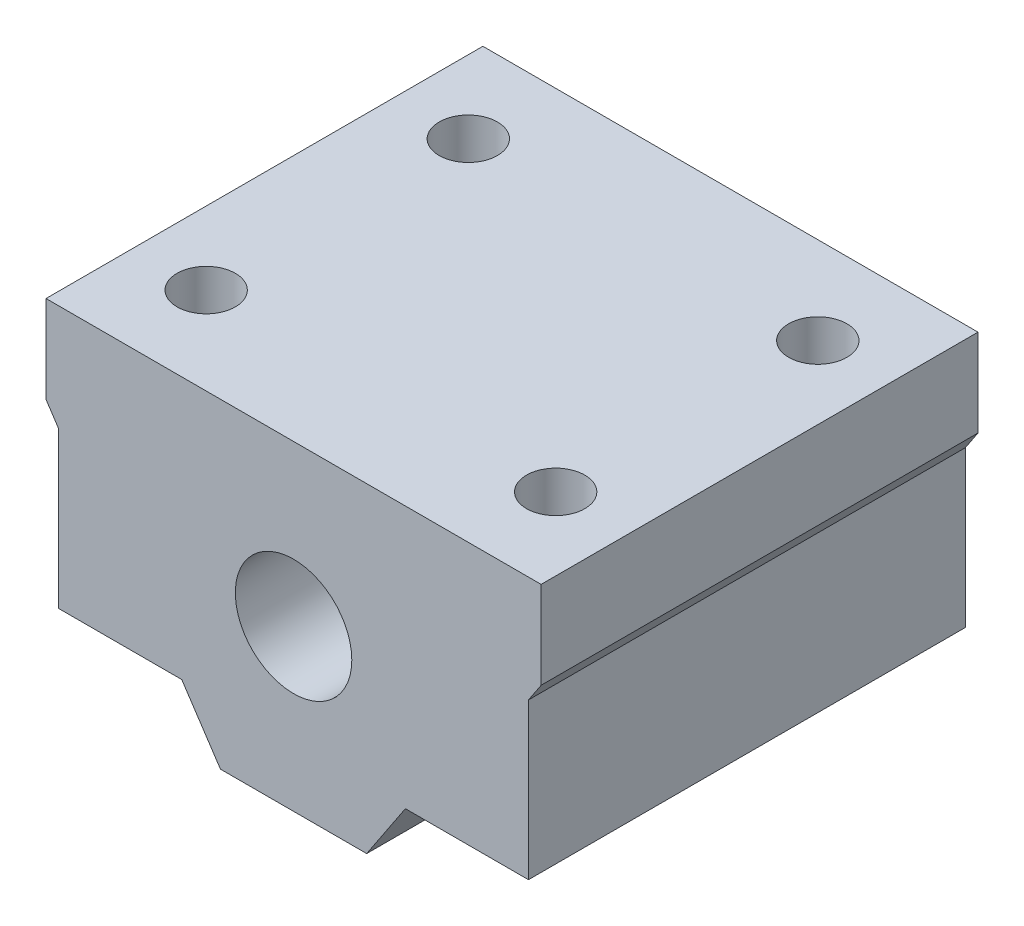
SolidWorks part; units mm, degrees
ref_plane "前视基准面" through (0, 0, 0) normal (0, 0, 1) x (1, 0, 0)
ref_plane "上视基准面" through (0, 0, 0) normal (0, 1, 0) x (1, 0, 0)
ref_plane "右视基准面" through (0, 0, 0) normal (1, 0, 0) x (0, 0, -1)
sketch "草图1" plane through (0, 0, 0) normal (0, 0, 1) x (1, 0, 0)
  line L0 (-10.9244, 0) -> (10.2906, 0) construction
  line L1 (17, 11) -> (-17, 11)
  line L2 (-17, 11) -> (-17, 5)
  line L3 (-17, 5) -> (-16.1309, 3.6913)
  line L4 (-16.1309, 3.6913) -> (-16.1309, -7)
  line L5 (-16.1309, -7) -> (-7.6782, -7)
  line L6 (-7.6782, -7) -> (-5.0218, -11)
  line L7 (-5.0218, -11) -> (5.0218, -11)
  line L8 (7.6782, -7) -> (5.0218, -11)
  line L9 (16.1309, -7) -> (7.6782, -7)
  line L10 (16.1309, 3.6913) -> (16.1309, -7)
  line L11 (17, 5) -> (16.1309, 3.6913)
  line L12 (17, 11) -> (17, 5)
  circle A0 centre (0, 0) radius 4
  point P12 (0, -11)
  dimension "D6" = 8
  dimension "D2" = 6
  dimension "D3" = 18
  dimension "D4" = 22
  dimension "D5" = 11
extrude "凸台-拉伸1" add sketch "草图1" along normal blind 30
sketch "草图2" plane through (0, 11, 0) normal (0, 1, 0) x (1, 0, 0)
  line L0 (17, 0) -> (-17, 0) construction
  line L1 (17, -30) -> (-17, -30) construction
  line L2 (-17, -30) -> (-17, 0) construction
  line L3 (17, -30) -> (17, 0) construction
  circle A0 centre (-12, -6) radius 2
  circle A1 centre (-12, -24) radius 2
  circle A2 centre (12, -6) radius 2
  circle A3 centre (12, -24) radius 2
  point P0 (-12, -6)
  point P1 (-12, -24)
  point P6 (12, -6)
  point P7 (12, -24)
  dimension "D5" = 5
  dimension "D1" = 6
  dimension "D2" = 6
  dimension "D3" = 24
  dimension "D4" = 24
  dimension "D6" = 5
extrude "切除-拉伸1" cut sketch "草图2" against normal blind 8
sketch "草图4" plane through (0, 11, 0) normal (0, 1, 0) x (1, 0, 0)
  circle A0 centre (-12, -6) radius 1.7
  circle A1 centre (-12, -24) radius 1.7
  circle A2 centre (12, -6) radius 1.7
  circle A3 centre (12, -24) radius 1.7
extrude "切除-拉伸2" cut sketch "草图4" against normal through all and the other way through all
